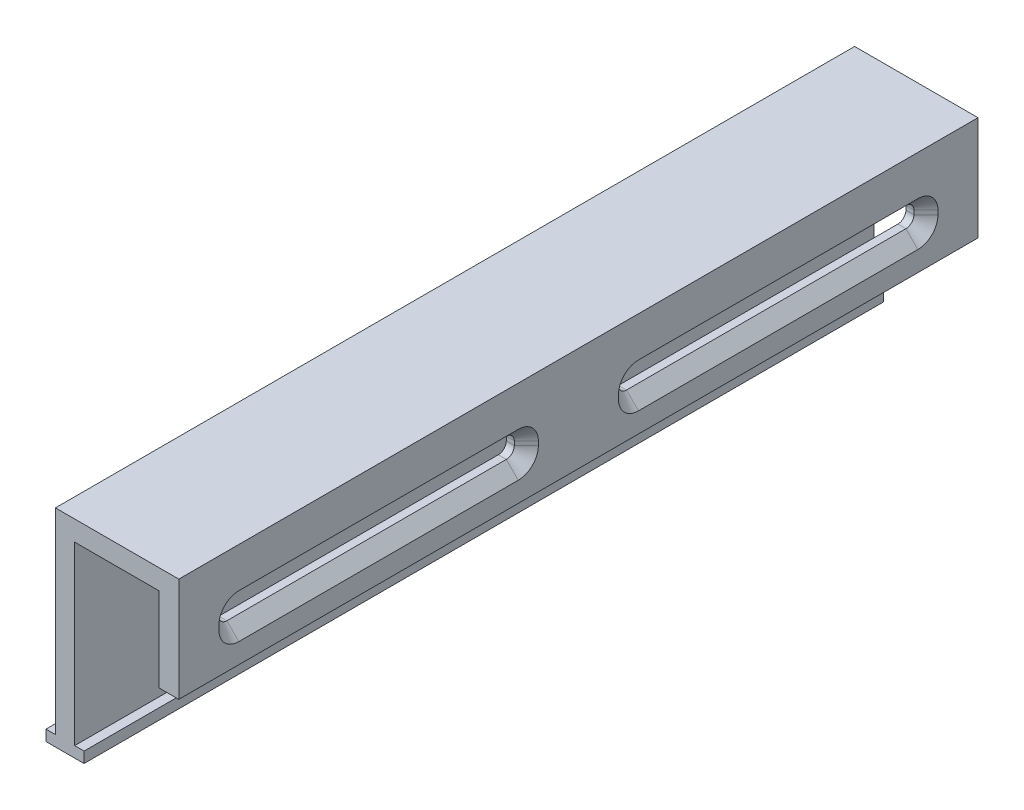
SolidWorks part; units mm, degrees
ref_plane "Front Plane" through (0, 0, 0) normal (0, 0, 1) x (1, 0, 0)
ref_plane "Top Plane" through (0, 0, 0) normal (0, 1, 0) x (1, 0, 0)
ref_plane "Right Plane" through (0, 0, 0) normal (1, 0, 0) x (0, 0, -1)
sketch "Sketch1" plane through (0, 0, 0) normal (0, 0, 1) x (1, 0, 0)
  line L0 (0, 0) -> (0, 49)
  line L5 (0, 49) -> (30.8, 49)
  line L6 (30.8, 49) -> (30.8, 23)
  line L7 (30.8, 23) -> (25.8, 23)
  line L8 (25.8, 23) -> (25.8, 44)
  line L9 (25.8, 44) -> (4.8, 44)
  line L10 (4.8, 44) -> (4.8, 0)
  line L12 (7.15, 0) -> (7.15, -2.7)
  line L13 (7.15, -2.7) -> (-2.35, -2.7)
  line L14 (-2.35, -2.7) -> (-2.35, 0)
  line L16 (0, 0) -> (-2.35, 0)
  line L17 (4.8, 0) -> (7.15, 0)
  dimension "D1" = 5
  dimension "D2" = 5
  dimension "D3" = 4.8
  dimension "D4" = 21
  dimension "D5" = 21
  dimension "D6" = 2.35
  dimension "D7" = 2.7
  dimension "D8" = 2.35
  dimension "D9" = 23
extrude "Boss-Extrude1" add sketch "Sketch1" against normal blind 199.5
sketch "Sketch2" plane through (30.8, 0, 0) normal (1, 0, 0) x (0, 0, -1)
  line L0 (99.75, 49) -> (99.75, 23) construction
  line L1 (199.5, 49) -> (0, 49) construction
  line L2 (199.5, 23) -> (0, 23) construction
  line L3 (199.5, 23) -> (199.5, 49) construction
  line L4 (0, 33.5) -> (199.5, 33.5) construction
  line L5 (0, 23) -> (0, 49) construction
  line L7 (15, 36) -> (84.75, 36)
  line L8 (13, 34) -> (13, 33)
  line L9 (15, 31) -> (84.75, 31)
  line L10 (86.75, 34) -> (86.75, 33)
  line L11 (114.75, 36) -> (184.5, 36)
  line L12 (112.75, 34) -> (112.75, 33)
  line L13 (114.75, 31) -> (184.5, 31)
  line L14 (186.5, 34) -> (186.5, 33)
  arc A8 (184.5, 31) -> (186.5, 33) centre (184.5, 33) ccw
  arc A9 (184.5, 36) -> (186.5, 34) centre (184.5, 34) cw
  arc A10 (112.75, 33) -> (114.75, 31) centre (114.75, 33) ccw
  arc A11 (114.75, 36) -> (112.75, 34) centre (114.75, 34) ccw
  arc A12 (84.75, 31) -> (86.75, 33) centre (84.75, 33) ccw
  arc A13 (84.75, 36) -> (86.75, 34) centre (84.75, 34) cw
  arc A14 (13, 33) -> (15, 31) centre (15, 33) ccw
  arc A15 (15, 36) -> (13, 34) centre (15, 34) ccw
  point P20 (13, 33.5)
  point P21 (112.75, 33.5)
  point P22 (0, 0)
  point P23 (0, 0)
  dimension "D2" = 99.75
  dimension "D3" = 15
  dimension "D4" = 2
  dimension "D5" = 10.5
  dimension "D9" = 15
  dimension "D11" = 15
  dimension "D12" = 15
  dimension "D13" = 5
extrude "Cut-Extrude1" cut sketch "Sketch2" against normal up to surface (5 mm away) up to face at (25.8, 33.5, -99.75)
chamfer "Chamfer1" distance 3 angle 45 16 edges at (30.8, 36, -149.625) (30.8, 35.4142, -113.3358) (30.8, 35.4142, -185.9142) (30.8, 33.5, -112.75) (30.8, 33.5, -186.5) (30.8, 31.5858, -113.3358) (30.8, 31.5858, -185.9142) (30.8, 31, -149.625) (30.8, 36, -49.875) (30.8, 35.4142, -13.5858) (30.8, 35.4142, -86.1642) (30.8, 33.5, -13) (30.8, 33.5, -86.75) (30.8, 31.5858, -13.5858) (30.8, 31.5858, -86.1642) (30.8, 31, -49.875)
